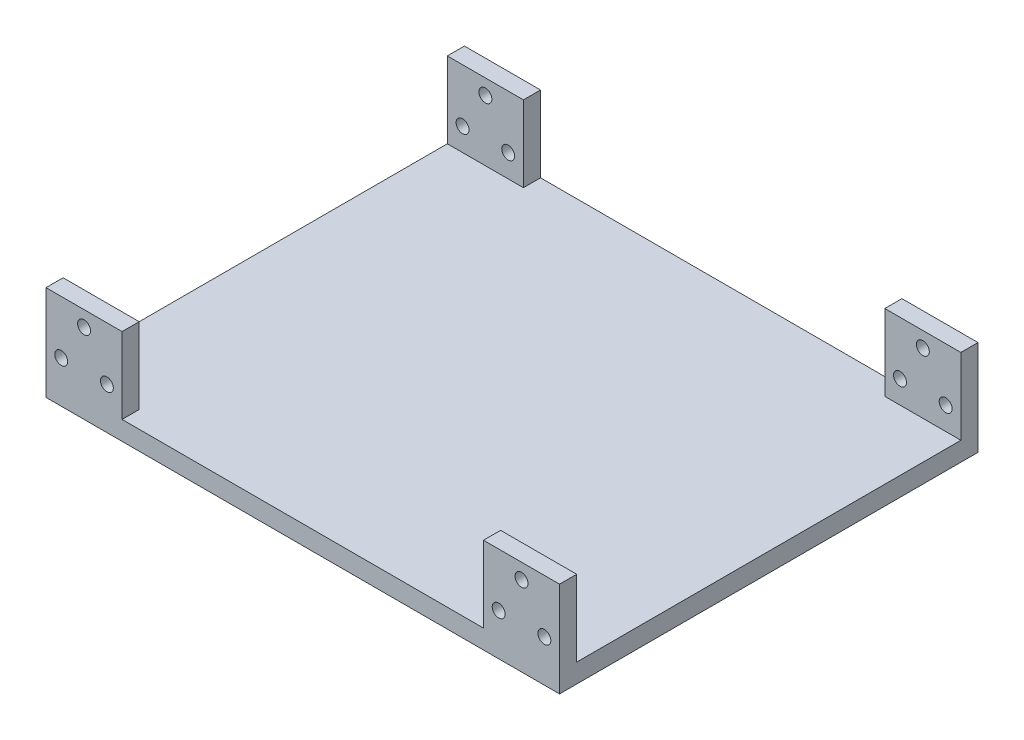
SolidWorks part; units mm, degrees
ref_plane "前视基准面" through (0, 0, 0) normal (0, 0, 1) x (1, 0, 0)
ref_plane "上视基准面" through (0, 0, 0) normal (0, 1, 0) x (1, 0, 0)
ref_plane "右视基准面" through (0, 0, 0) normal (1, 0, 0) x (0, 0, -1)
other "Configuration Table"
sketch "草图1" plane through (0, 0, 0) normal (0, 1, 0) x (1, 0, 0)
  line L1 (-67.5, -55) -> (67.5, -55)
  line L2 (-67.5, -55) -> (-67.5, 55)
  line L3 (-67.5, 55) -> (67.5, 55)
  line L4 (67.5, -55) -> (67.5, 55)
  line L5 (-67.5, -55) -> (67.5, 55) construction
  line L6 (-67.5, 55) -> (67.5, -55) construction
  circle A0 centre (0, 0) radius 45.1 construction
  point P0 (0, 0)
  dimension "D3" = 90.2
  dimension "D1" = 135
  dimension "D2" = 110
extrude "凸台-拉伸1" add sketch "草图1" along normal blind 5
sketch "草图2" plane through (0, 5, 0) normal (0, 1, 0) x (1, 0, 0)
  line L0 (0, 74.8332) -> (0, -74.7033) construction
  line L1 (67.5, 55) -> (47.5, 55)
  line L2 (67.5, 55) -> (67.5, 50.5)
  line L3 (67.5, 50.5) -> (47.5, 50.5)
  line L4 (47.5, 55) -> (47.5, 50.5)
  line L5 (-98.2819, 0) -> (125.7529, 0) construction
  line L6 (-47.5, 55) -> (-47.5, 50.5)
  line L7 (-67.5, 55) -> (-67.5, 50.5)
  line L8 (-67.5, 55) -> (-47.5, 55)
  line L9 (-67.5, 50.5) -> (-47.5, 50.5)
  line L10 (-67.5, -50.5) -> (-47.5, -50.5)
  line L11 (-67.5, -55) -> (-47.5, -55)
  line L12 (-67.5, -55) -> (-67.5, -50.5)
  line L13 (-47.5, -55) -> (-47.5, -50.5)
  line L14 (47.5, -55) -> (47.5, -50.5)
  line L15 (67.5, -50.5) -> (47.5, -50.5)
  line L16 (67.5, -55) -> (67.5, -50.5)
  line L17 (67.5, -55) -> (47.5, -55)
  dimension "D1" = 20
  dimension "D2" = 4.5
extrude "凸台-拉伸2" add sketch "草图2" along normal blind 20
sketch "草图3" plane through (0, 0, -55) normal (0, 0, -1) x (-1, 0, 0)
  line L0 (-47.5, 5) -> (47.5, 5) construction
  line L1 (57.5, 26.3093) -> (57.5, -1.1591) construction
  line L3 (67.5, 25) -> (67.5, 0) construction
  line L4 (0, 19.4042) -> (0, -9.4424) construction
  circle A0 centre (57.5, 21) radius 1.7
  circle A1 centre (51.5, 11) radius 1.7
  circle A2 centre (63.5, 11) radius 1.7
  circle A3 centre (-51.5, 11) radius 1.7
  circle A4 centre (-63.5, 11) radius 1.7
  circle A5 centre (-57.5, 21) radius 1.7
  dimension "D2" = 3.4
  dimension "D4" = 3.4
  dimension "D7" = 3.4
  dimension "D1" = 16
  dimension "D3" = 6
  dimension "D5" = 12
  dimension "D6" = 10
extrude "切除-拉伸1" cut sketch "草图3" against normal blind 130
sketch "草图4" plane through (0, 0, 0) normal (0, -1, 0) x (1, 0, 0)
  circle A0 centre (0, 0) radius 45.1
  circle A1 centre (0, 0) radius 32.45
  dimension "D1" = 90.2
  dimension "D2" = 64.9
extrude "切除-拉伸2" cut sketch "草图4" against normal blind 2
